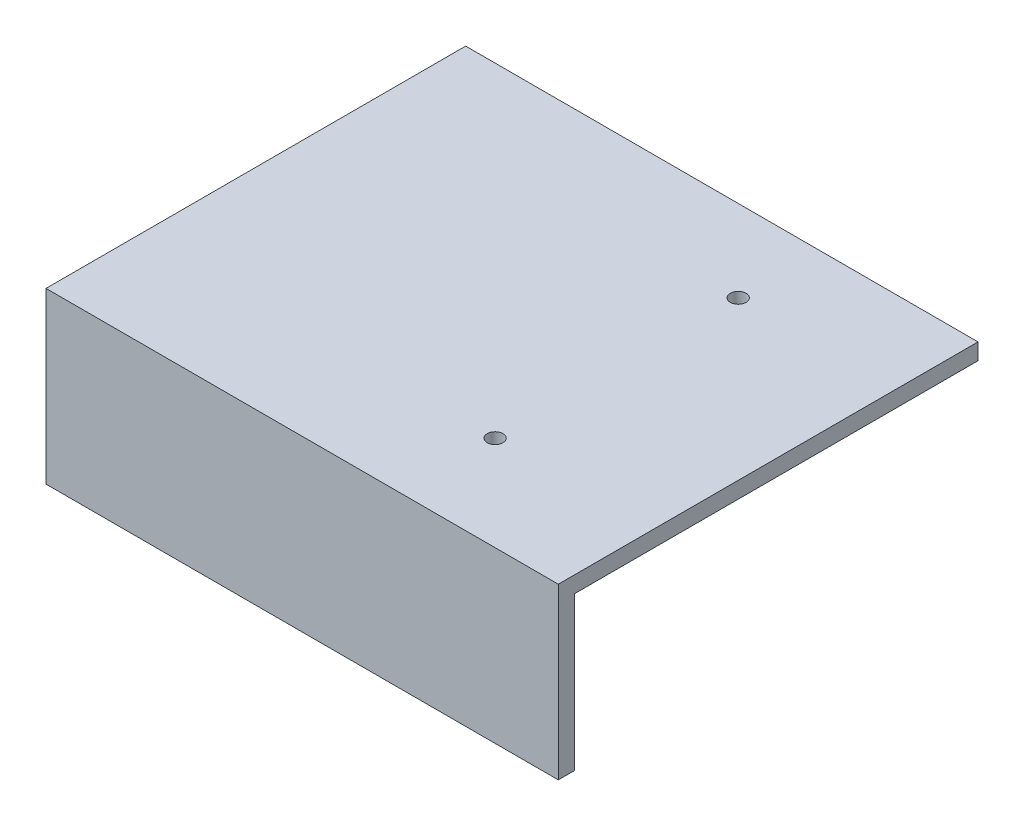
SolidWorks part; units mm, degrees
ref_plane "Front Plane" through (0, 0, 0) normal (0, 0, 1) x (1, 0, 0)
ref_plane "Top Plane" through (0, 0, 0) normal (0, 1, 0) x (1, 0, 0)
ref_plane "Right Plane" through (0, 0, 0) normal (1, 0, 0) x (0, 0, -1)
sketch "Sketch1" plane through (0, 0, 0) normal (0, 1, 0) x (1, 0, 0)
  line L1 (-47, -38.5) -> (47, -38.5)
  line L2 (-47, -38.5) -> (-47, 38.5)
  line L3 (-47, 38.5) -> (47, 38.5)
  line L4 (47, -38.5) -> (47, 38.5)
  line L5 (-47, -38.5) -> (47, 38.5) construction
  line L6 (-47, 38.5) -> (47, -38.5) construction
  point P0 (0, 0)
  dimension "D1" = 94
  dimension "D2" = 77
extrude "Boss-Extrude1" add sketch "Sketch1" along normal blind 3
sketch "Sketch2" plane through (0, 0, 0) normal (0, -1, 0) x (1, 0, 0)
  line L0 (-47, -38.5) -> (-47, 38.5) construction
  line L1 (-47, 35.5) -> (47, 35.5)
  line L2 (-47, 35.5) -> (-47, 38.5)
  line L3 (-47, 38.5) -> (47, 38.5)
  line L4 (47, 35.5) -> (47, 38.5)
  line L5 (-47, 35.5) -> (47, 38.5) construction
  line L6 (-47, 38.5) -> (47, 35.5) construction
  point P0 (0, 37)
  dimension "D1" = 3
extrude "Boss-Extrude2" add sketch "Sketch2" along normal blind 28.1
sketch "Sketch3" plane through (0, 3, 0) normal (0, 1, 0) x (1, 0, 0)
  line L0 (47, 38.5) -> (-47, 38.5) construction
  line L1 (47, -38.5) -> (47, 38.5) construction
  circle A0 centre (18, 23.5) radius 1.45
  dimension "D1" = 2.9
  dimension "D2" = 15
  dimension "D3" = 29
extrude "Cut-Extrude1" cut sketch "Sketch3" against normal through all
pattern_linear "LPattern1" count 2 spacing 44.6 along (0, 0, 1) of "Cut-Extrude1"
